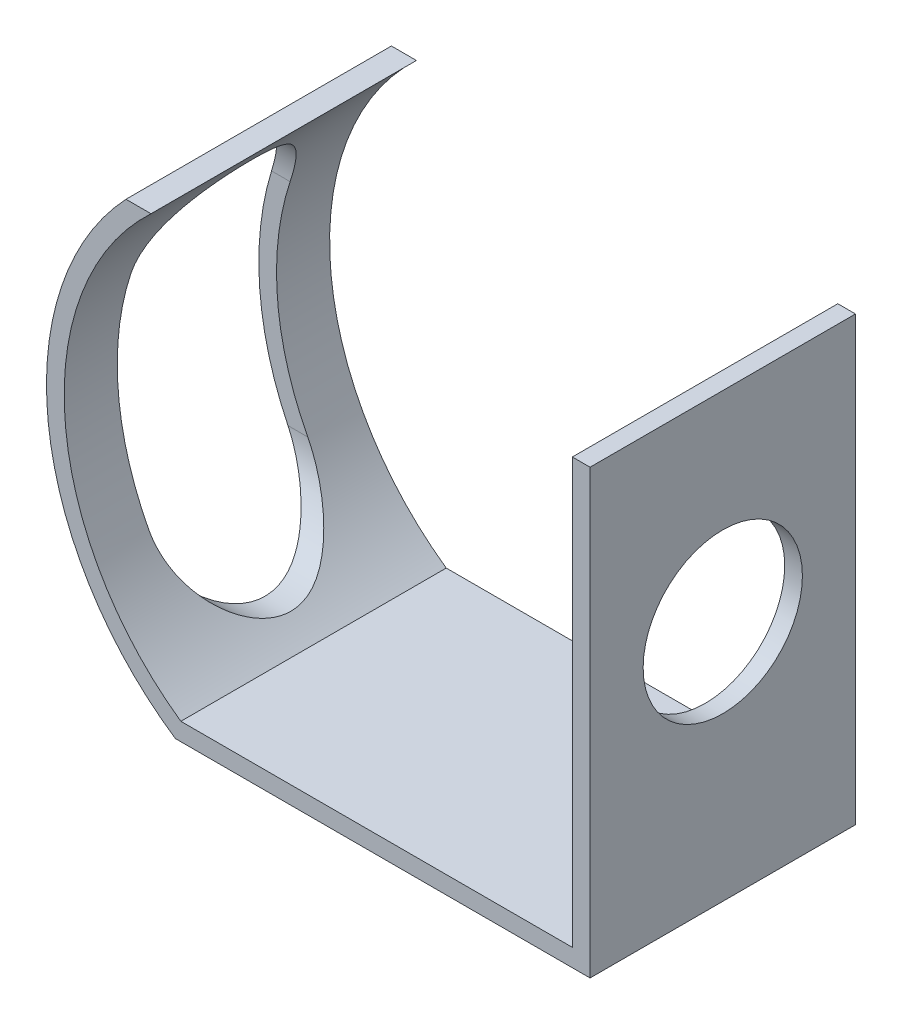
SolidWorks part; units mm, degrees
ref_plane "Alzado" through (0, 0, 0) normal (0, 0, 1) x (1, 0, 0)
ref_plane "Planta" through (0, 0, 0) normal (0, 1, 0) x (1, 0, 0)
ref_plane "Vista lateral" through (0, 0, 0) normal (1, 0, 0) x (0, 0, -1)
sketch "Croquis1" plane through (0, 0, 0) normal (0, 0, 1) x (1, 0, 0)
  line L0 (-10, 250) -> (0, 250)
  line L1 (0, 250) -> (0, 0)
  line L2 (0, 0) -> (-234.3789, 0)
  line L3 (-262.27, 250) -> (-248.1112, 250)
  line L4 (-10, 250) -> (-10, 10)
  line L5 (-10, 10) -> (-231.2722, 10)
  arc A0 (-262.27, 250) -> (-234.3789, 0) centre (-142.1863, 136.8413) ccw
  arc A1 (-248.1112, 250) -> (-231.2722, 10) centre (-142.1863, 136.8413) ccw
  dimension "D2" = 10
  dimension "D3" = 10
  dimension "D4" = 165
  dimension "D1" = 10
  dimension "D5" = 250
extrude "Saliente-Extruir1" add sketch "Croquis1" along normal mid plane 150
sketch "Croquis2" plane through (0, 0, 0) normal (1, 0, 0) x (0, 0, -1)
  circle A0 centre (0, 136.8412) radius 45 construction
  circle A1 centre (0, 136.8412) radius 45
extrude "Cortar-Extruir1" cut sketch "Croquis2" against normal up to next
sketch "Croquis3" plane through (-10, 0, 0) normal (-1, 0, 0) x (0, 0, 1)
  line L2 (45, 185) -> (45, 65)
  line L4 (-45, 185) -> (-45, 65)
  line L5 (0, 230) -> (0, 250) construction
  line L7 (-75, 125) -> (75, 125) construction
  line L8 (75, 250) -> (-75, 250) construction
  line L9 (-75, 250) -> (-75, 0) construction
  line L10 (75, 0) -> (75, 250) construction
  line L11 (0, 20) -> (0, 0) construction
  circle A0 centre (0, 136.8412) radius 45 construction
  arc A1 (45, 185) -> (-45, 185) centre (0, 185) ccw
  arc A2 (45, 65) -> (-45, 65) centre (0, 65) cw
  dimension "D1" = 120
extrude "Cortar-Extruir2" cut sketch "Croquis3" along normal up to next
